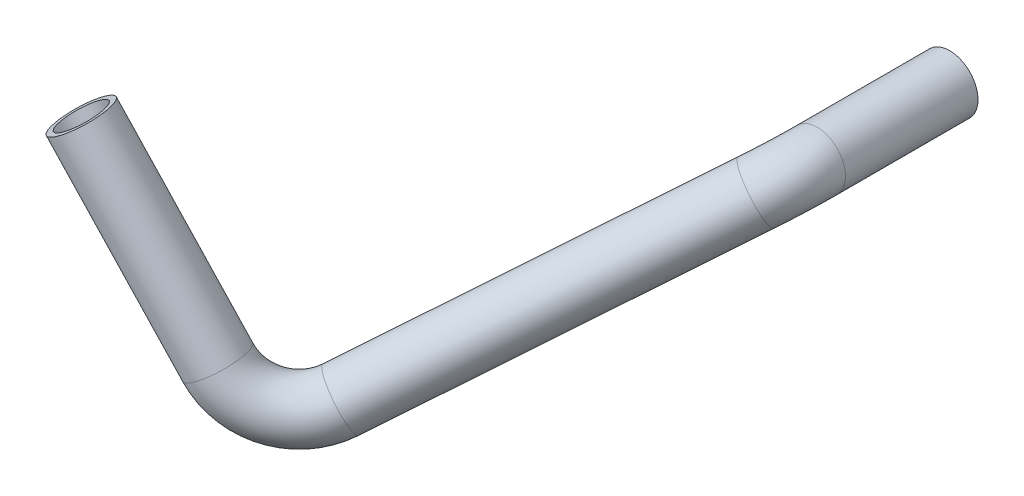
SolidWorks part; units mm, degrees
ref_plane "Front" through (0, 0, 0) normal (0, 0, 1) x (1, 0, 0)
ref_plane "Top" through (0, 0, 0) normal (0, 1, 0) x (1, 0, 0)
ref_plane "Side" through (0, 0, 0) normal (1, 0, 0) x (0, 0, -1)
sketch "PipeSketch" plane through (0, 0, 0) normal (0, 0, 1) x (1, 0, 0)
  circle A0 centre (0, 0) radius 16.764
  circle A1 centre (0, 0) radius 13.3858
  dimension "OuterDiameter" = 33.528
  dimension "InnerDiameter" = 26.7716
extrude "Extrusion" add sketch "PipeSketch" along normal blind 78.4331
sketch "FilterSketch" plane through (0, 0, 0) normal (0, 0, 1) x (1, 0, 0)
  circle A0 centre (0, 0) radius 12.7 construction
  dimension "NominalDiameter" = 25.4
sketch "草图1" plane through (0, 0, 78.4331) normal (0, 0, 1) x (1, 0, 0)
  line L0 (-29.099, -24.5938) -> (-4.5052, -53.6929) construction
  circle A0 centre (0, 0) radius 16.764 construction
  circle A1 centre (0, 0) radius 13.3858 construction
  circle A2 centre (0, 0) radius 16.764
  circle A3 centre (0, 0) radius 13.3858
revolve "旋转1" add sketch "草图1" angle 45.819 about L0
sketch "草图2" plane through (-44.9051, -37.9528, 57.1373) normal (-0.5477, -0.4629, 0.6969) x (0.8367, -0.3031, 0.4562)
  circle A0 centre (43.1308, 52.3059) radius 13.3858 construction
  circle A1 centre (43.1308, 52.3059) radius 16.764 construction
  circle A2 centre (43.1308, 52.3059) radius 13.3858
  circle A3 centre (43.1308, 52.3059) radius 16.764
extrude "凸台-拉伸1" add sketch "草图2" along normal blind 197.4387
sketch "草图3" plane through (-153.0467, -129.3517, 194.737) normal (-0.5477, -0.4629, 0.6969) x (0.8367, -0.3031, 0.4562)
  line L0 (18.1885, 81.1068) -> (-10.6124, 56.1645) construction
  circle A0 centre (43.1308, 52.3059) radius 16.764 construction
  circle A1 centre (43.1308, 52.3059) radius 13.3858 construction
  circle A2 centre (43.1308, 52.3059) radius 16.764
  circle A3 centre (43.1308, 52.3059) radius 13.3858
revolve "旋转2" add sketch "草图3" angle 90 about L0
sketch "草图4" plane through (-27.0596, 40.9099, 5.9074) normal (-0.5477, 0.8281, 0.1196) x (0.8367, 0.5421, 0.0783)
  circle A0 centre (-157.3372, -283.7865) radius 13.3858 construction
  circle A1 centre (-157.3372, -283.7865) radius 16.764 construction
  circle A2 centre (-157.3372, -283.7865) radius 13.3858
  circle A3 centre (-157.3372, -283.7865) radius 16.764
extrude "凸台-拉伸2" add sketch "草图4" along normal blind 120.9237
